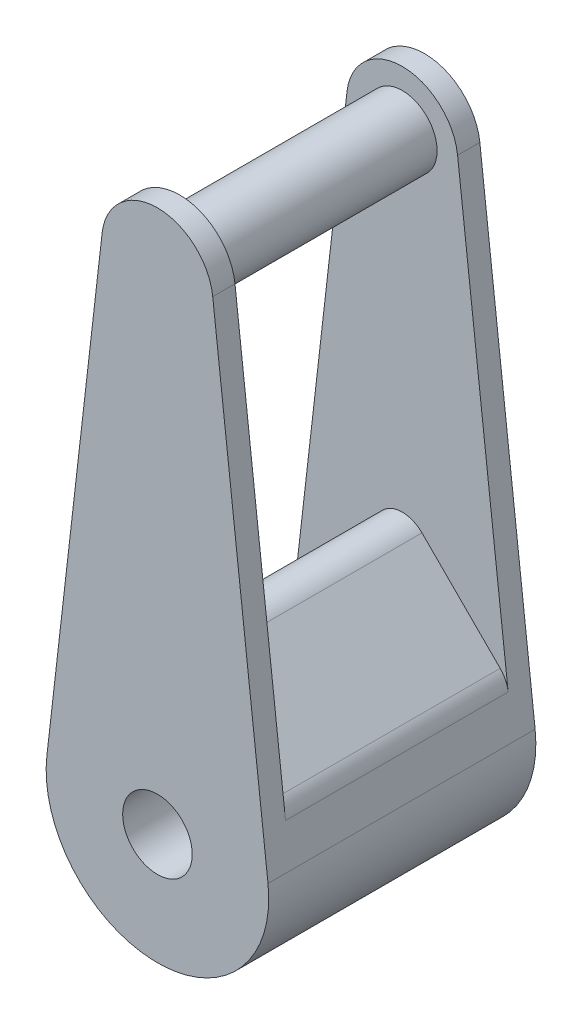
SolidWorks part; units mm, degrees
ref_plane "Front Plane" through (0, 0, 0) normal (0, 0, 1) x (1, 0, 0)
ref_plane "Top Plane" through (0, 0, 0) normal (0, 1, 0) x (1, 0, 0)
ref_plane "Right Plane" through (0, 0, 0) normal (1, 0, 0) x (0, 0, -1)
sketch "Sketch1" plane through (0, 0, 0) normal (0, 0, 1) x (1, 0, 0)
  circle A0 centre (0, 0) radius 12.5
  dimension "D1" = 25
extrude "Boss-Extrude1" add sketch "Sketch1" along normal mid plane 80
sketch "Sketch2" plane through (0, 0, 40) normal (0, 0, 1) x (1, 0, 0)
  line L0 (0, 0) -> (0, -175) construction
  line L1 (-19.869, 2.2857) -> (-39.7379, -170.4286)
  line L2 (19.869, 2.2857) -> (39.7379, -170.4286)
  arc A0 (19.869, 2.2857) -> (-19.869, 2.2857) centre (0, 0) ccw
  arc A1 (-39.7379, -170.4286) -> (39.7379, -170.4286) centre (0, -175) ccw
  dimension "D1" = 40
  dimension "D3" = 80
  dimension "D2" = 175
extrude "Boss-Extrude2" add sketch "Sketch2" along normal blind 8 contours L2 A1 L1 A0
mirror "Mirror1" about plane through (0, 0, 0) normal (0, 0, 1) of "Boss-Extrude2"
sketch "Sketch4" plane through (0, 0, -40) normal (0, 0, 1) x (1, 0, 0)
  line L0 (0, -175) -> (0, -114.5749) construction
  line L1 (-7.0711, -121.6459) -> (-35.178, -149.7528)
  line L2 (-19.869, 2.2857) -> (-39.7379, -170.4286)
  line L3 (39.7379, -170.4286) -> (19.869, 2.2857)
  line L4 (-38.0414, -155.681) -> (-39.7379, -170.4286)
  line L5 (39.7379, -170.4286) -> (38.0414, -155.681)
  line L6 (7.0711, -121.6459) -> (35.178, -149.7528)
  arc A0 (7.0711, -121.6459) -> (-7.0711, -121.6459) centre (0, -128.717) ccw
  arc A1 (38.0414, -155.681) -> (35.178, -149.7528) centre (28.1069, -156.8239) ccw
  arc A2 (19.869, 2.2857) -> (-19.869, 2.2857) centre (0, 0) ccw
  arc A3 (-39.7379, -170.4286) -> (39.7379, -170.4286) centre (0, -175) ccw
  arc A5 (-39.7379, -170.4286) -> (39.7379, -170.4286) centre (0, -175) ccw
  arc A6 (-38.0414, -155.681) -> (-35.178, -149.7528) centre (-28.1069, -156.8239) cw
  dimension "D2" = 10
  dimension "D1" = 0
extrude "Boss-Extrude3" add sketch "Sketch4" along normal up to surface (80 mm away) up to face at (12.5, 0, 40)
sketch "Sketch5" plane through (0, 0, -48) normal (0, 0, -1) x (-1, 0, 0)
  circle A0 centre (0, -175) radius 12.5
  dimension "D2" = 25
extrude "Cut-Extrude1" cut sketch "Sketch5" against normal up to surface (96 mm away) up to face at (0, -90.7857, 48)
